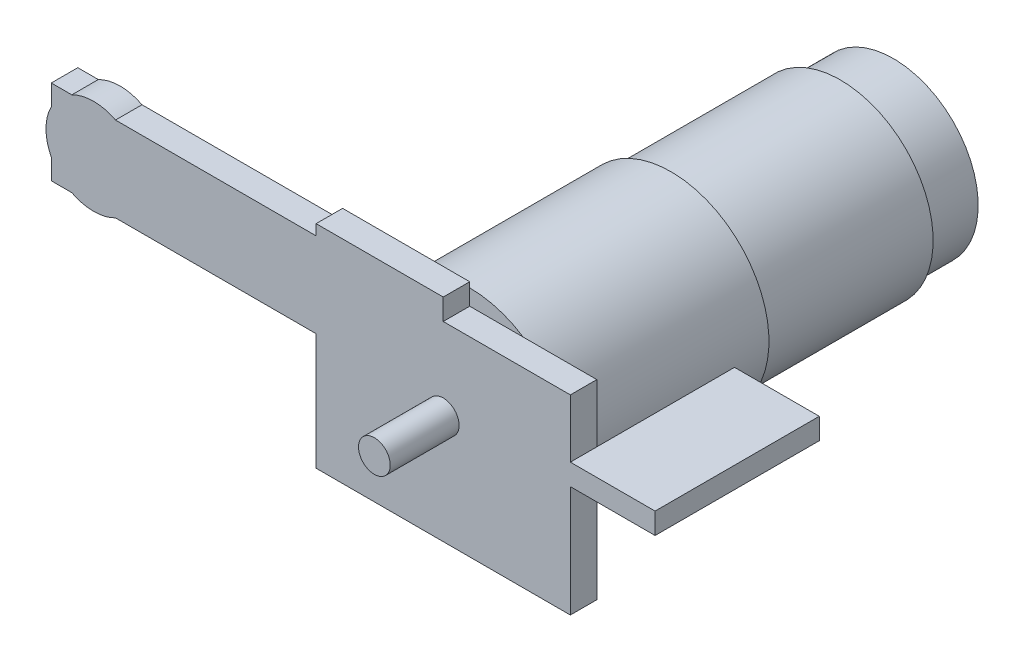
SolidWorks part; units mm, degrees
ref_plane "Front Plane" through (0, 0, 0) normal (0, 0, 1) x (1, 0, 0)
ref_plane "Top Plane" through (0, 0, 0) normal (0, 1, 0) x (1, 0, 0)
ref_plane "Right Plane" through (0, 0, 0) normal (1, 0, 0) x (0, 0, -1)
ref_plane "PL_Y_20p50" through (0, 20.5, 0) normal (0, 1, 0) x (1, 0, 0)
sketch "SK_P01_Gearmotor37Dwith64CPRenc" plane through (0, 20.5, 0) normal (0, 1, 0) x (1, 0, 0)
  line L0 (17.5, -49) -> (20.5, -49)
  line L1 (20.5, -49) -> (20.5, -31)
  line L2 (20.5, -31) -> (36, -31)
  line L3 (36, -31) -> (36, 7)
  line L4 (36, 7) -> (35, 7)
  line L5 (35, 7) -> (35, 39)
  line L6 (35, 39) -> (33.5, 39)
  line L7 (33.5, 39) -> (33.5, 49)
  line L8 (33.5, 49) -> (17.5, 49)
  line L9 (17.5, 49) -> (17.5, -49)
  line L10 (17.5, 54) -> (17.5, -54) construction
revolve "P01_Gearmotor37Dwith64CPRenc" add sketch "SK_P01_Gearmotor37Dwith64CPRenc" angle 360 about L10
sketch "SK_P02_Moduleplate" plane through (0, 0, 0) normal (0, 1, 0) x (1, 0, 0)
  line L0 (-6.5, -36) -> (17.5, -36)
  line L1 (17.5, -36) -> (17.5, -31)
  line L2 (17.5, -31) -> (-6.5, -31)
  line L3 (-6.5, -31) -> (-6.5, -36)
extrude "P02_Moduleplate" add sketch "SK_P02_Moduleplate" along normal blind 40
sketch "SK_P03_Moduleplate" plane through (0, 0, 0) normal (0, 1, 0) x (1, 0, 0)
  line L0 (17.5, -36) -> (41.5, -36)
  line L1 (41.5, -36) -> (41.5, -31)
  line L2 (41.5, -31) -> (17.5, -31)
  line L3 (17.5, -31) -> (17.5, -36)
extrude "P03_Moduleplate" add sketch "SK_P03_Moduleplate" along normal blind 36
sketch "SK_P04_Trailingarm" plane through (0, 0, 0) normal (0, 1, 0) x (1, 0, 0)
  line L0 (-56.5, -36) -> (-6.5, -36)
  line L1 (-6.5, -36) -> (-6.5, -31)
  line L2 (-6.5, -31) -> (-56.5, -31)
  line L3 (-56.5, -31) -> (-56.5, -36)
extrude "P04_Trailingarm" add sketch "SK_P04_Trailingarm" along normal blind 16 from offset 22
sketch "SK_P05_Pivotboss" plane through (0, 0, 0) normal (0, 0, 1) x (1, 0, 0)
  circle A0 centre (-48.5, 30) radius 9
extrude "P05_Pivotboss" add sketch "SK_P05_Pivotboss" along normal blind 5 from offset 31
sketch "SK_P06_Springtab" plane through (0, 0, 0) normal (0, 1, 0) x (1, 0, 0)
  line L0 (41.5, -36) -> (57.5, -36)
  line L1 (57.5, -36) -> (57.5, -5)
  line L2 (57.5, -5) -> (41.5, -5)
  line L3 (41.5, -5) -> (41.5, -36)
extrude "P06_Springtab" add sketch "SK_P06_Springtab" along normal blind 4 from offset 21
